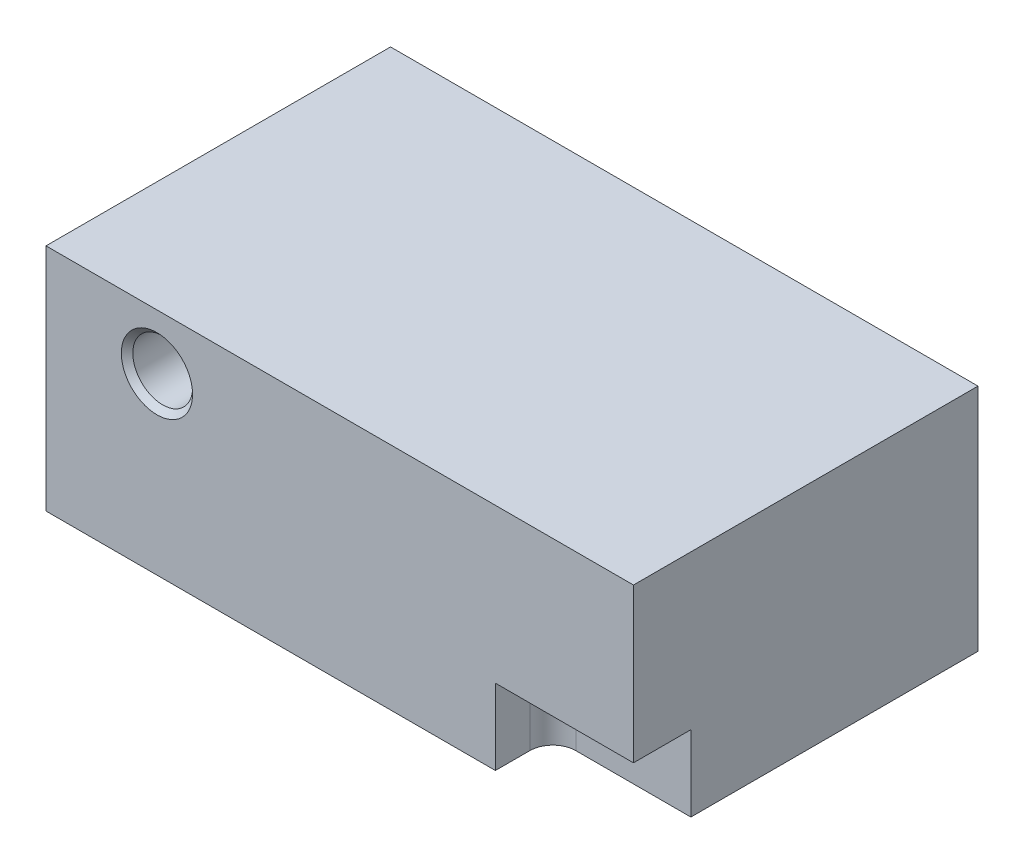
SolidWorks part; units mm, degrees
ref_plane "Front Plane" through (0, 0, 0) normal (0, 0, 1) x (1, 0, 0)
ref_plane "Top Plane" through (0, 0, 0) normal (0, 1, 0) x (1, 0, 0)
ref_plane "Right Plane" through (0, 0, 0) normal (1, 0, 0) x (0, 0, -1)
sketch "Sketch1" plane through (0, 0, 0) normal (0, 1, 0) x (1, 0, 0)
  line L1 (0, 0) -> (1299.2214, 0)
  line L2 (0, 0) -> (0, -762)
  line L3 (0, -762) -> (1299.2214, -762)
  line L4 (1299.2214, 0) -> (1299.2214, -762)
  dimension "D1" = 1299.2214
  dimension "D2" = 762
extrude "Boss-Extrude2" add sketch "Sketch1" along normal blind 508
sketch "Sketch3" plane through (0, 0, 762) normal (0, 0, 1) x (1, 0, 0)
  circle A0 centre (199.4006, 376.8047) radius 90.1106
extrude "Boss-Extrude4" add sketch "Sketch3" against normal through all
sketch "Sketch4" plane through (0, 0, 762) normal (0, 0, 1) x (1, 0, 0)
  circle A0 centre (245.3956, 385.7832) radius 66.0656
extrude "Cut-Extrude1" cut sketch "Sketch4" against normal through all
chamfer "Chamfer3" distance 12.7 angle 45 2 edges at (311.4612, 385.7832, 762) (311.4612, 385.7832, 0)
sketch "Sketch5" plane through (0, 0, 762) normal (0, 0, 1) x (1, 0, 0)
  line L1 (1299.2214, 0) -> (993.8861, 0)
  line L2 (1299.2214, 0) -> (1299.2214, 167.3927)
  line L3 (1299.2214, 167.3927) -> (993.8861, 167.3927)
  line L4 (993.8861, 0) -> (993.8861, 167.3927)
extrude "Cut-Extrude2" cut sketch "Sketch5" against normal blind 127
fillet "Fillet3" radius 50.8 1 edges at (993.8861, 83.6964, 635)
